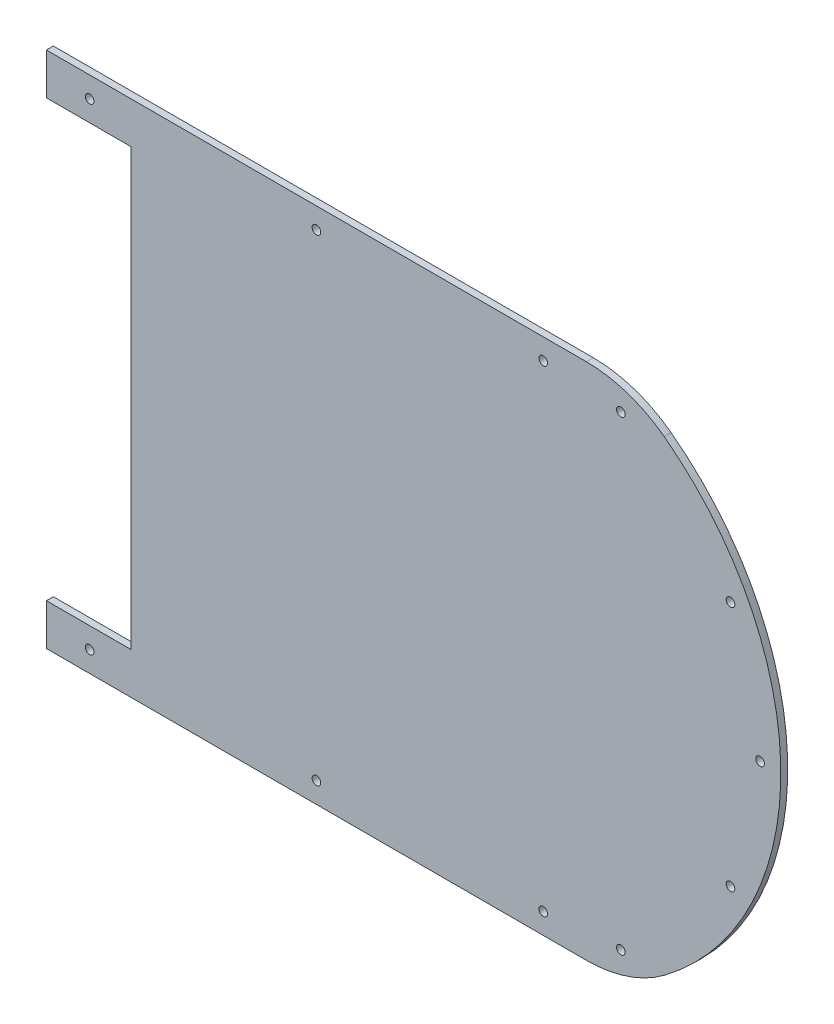
SolidWorks part; units mm, degrees
material "Acrylic (Medium-high impact)"
ref_plane "Front Plane" through (0, 0, 0) normal (0, 0, 1) x (1, 0, 0)
ref_plane "Top Plane" through (0, 0, 0) normal (0, 1, 0) x (1, 0, 0)
ref_plane "Right Plane" through (0, 0, 0) normal (1, 0, 0) x (0, 0, -1)
sketch "Sketch1" plane through (0, 0, 0) normal (0, 0, 1) x (1, 0, 0)
  line L29 (0, -122.4747) -> (312.5, -122.4747)
  line L30 (312.5, 177.5253) -> (0, 177.5253)
  line L31 (0, -122.4747) -> (312.5, -122.4747)
  line L32 (312.5, 177.5253) -> (0, 177.5253)
  line L36 (312.5, 153.5253) -> (0, 153.5253)
  line L37 (49, 153.5253) -> (0, 153.5253)
  line L38 (49, 153.5253) -> (49, -98.4747)
  line L39 (0, -98.4747) -> (312.5, -98.4747)
  line L40 (0, -98.4747) -> (49, -98.4747)
  line L41 (0, 177.5253) -> (0, 153.5253)
  line L42 (0, -98.4747) -> (0, -122.4747)
  arc A33 (312.5, -122.4747) -> (357.5, -107.4747) centre (312.5, -47.4747) ccw
  arc A34 (357.5, -107.4747) -> (357.5, 162.5253) centre (256.25, 27.5253) ccw
  arc A35 (357.5, 162.5253) -> (312.5, 177.5253) centre (312.5, 102.5253) ccw
  arc A36 (312.5, -122.4747) -> (357.5, -107.4747) centre (312.5, -47.4747) ccw
  arc A37 (357.5, -107.4747) -> (357.5, 162.5253) centre (256.25, 27.5253) ccw
  arc A38 (357.5, 162.5253) -> (312.5, 177.5253) centre (312.5, 102.5253) ccw
  circle A47 centre (25, 165.5253) radius 2.5
  circle A48 centre (25, 165.5253) radius 2.5
  circle A50 centre (156.25, 165.5253) radius 2.5
  circle A51 centre (156.25, 165.5253) radius 2.5
  circle A54 centre (287.5, 165.5253) radius 2.5
  circle A55 centre (287.5, 165.5253) radius 2.5
  circle A57 centre (332.4223, 162.2923) radius 2.5
  circle A58 centre (332.4223, 162.2923) radius 2.5
  circle A60 centre (395.888, 98.7418) radius 2.5
  circle A61 centre (395.888, 98.7418) radius 2.5
  circle A63 centre (413, 27.5253) radius 2.5
  circle A64 centre (413, 27.5253) radius 2.5
  circle A66 centre (395.888, -43.6913) radius 2.5
  circle A67 centre (395.888, -43.6913) radius 2.5
  circle A69 centre (332.4223, -107.2418) radius 2.5
  circle A70 centre (332.4223, -107.2418) radius 2.5
  circle A72 centre (287.5, -110.4747) radius 2.5
  circle A73 centre (287.5, -110.4747) radius 2.5
  circle A75 centre (156.25, -110.4747) radius 2.5
  circle A76 centre (156.25, -110.4747) radius 2.5
  circle A78 centre (25, -110.4747) radius 2.5
  circle A79 centre (25, -110.4747) radius 2.5
  dimension "D1" = 0
  dimension "D2" = 0
  dimension "D3" = 0
  dimension "D4" = 0
  dimension "D5" = 0
  dimension "D6" = 0
  dimension "D7" = 0
  dimension "D8" = 0
  dimension "D9" = 0
  dimension "D10" = 0
  dimension "D11" = 0
  dimension "D12" = 0
  dimension "D13" = 0
  dimension "D14" = 0
extrude "Boss-Extrude1" add sketch "Sketch1" along normal blind 4
